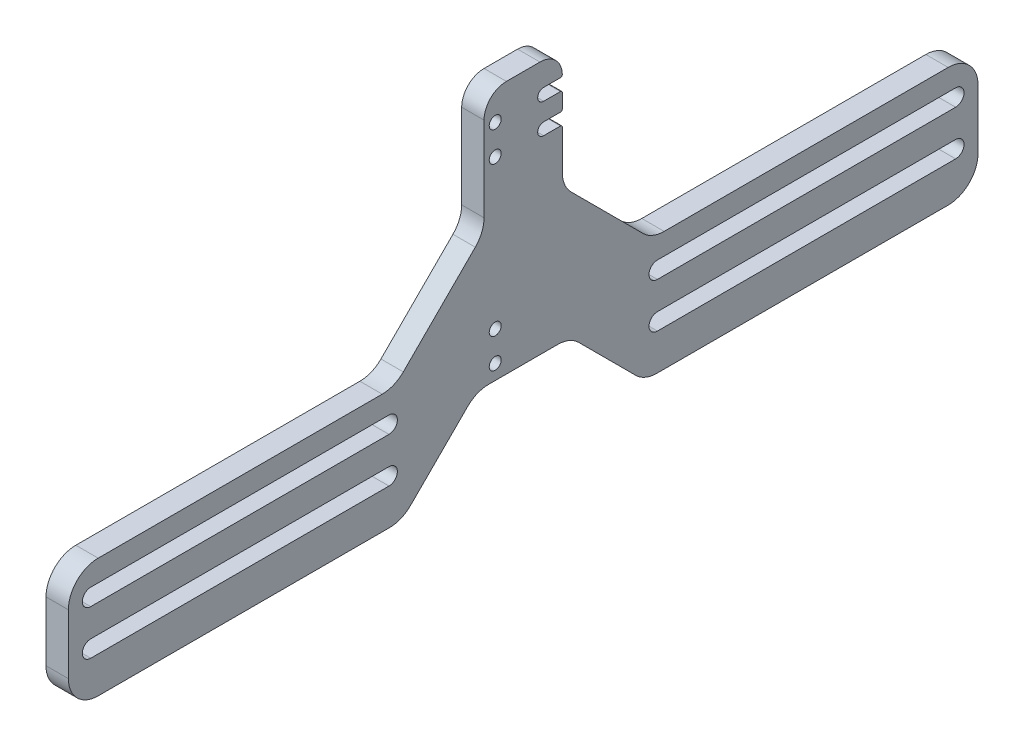
SolidWorks part; units mm, degrees
material "6061-T6 (SS)"
ref_plane "Front Plane" through (0, 0, 0) normal (0, 0, 1) x (1, 0, 0)
ref_plane "Top Plane" through (0, 0, 0) normal (0, 1, 0) x (1, 0, 0)
ref_plane "Right Plane" through (0, 0, 0) normal (1, 0, 0) x (0, 0, -1)
sketch "Sketch1" plane through (0, 0, 0) normal (1, 0, 0) x (0, 0, -1)
  line L0 (-193.675, 0) -> (193.675, 0)
  line L1 (193.675, 0) -> (193.675, 50.8)
  line L2 (193.675, 50.8) -> (54.7688, 50.8)
  line L5 (16.6687, 139.7) -> (-16.6687, 139.7)
  line L8 (-54.7688, 50.8) -> (-193.675, 50.8)
  line L9 (-193.675, 50.8) -> (-193.675, 0)
  line L10 (0, 139.7) -> (0, 0) construction
  line L13 (-16.6687, 139.7) -> (-16.6687, 88.9)
  line L14 (-16.6687, 88.9) -> (-54.7688, 50.8)
  line L15 (16.6687, 139.7) -> (16.6688, 88.9)
  line L16 (16.6688, 88.9) -> (54.7688, 50.8)
  dimension "D1" = 50.8
  dimension "D2" = 33.3375
  dimension "D3" = 193.675
  dimension "D4" = 45
  dimension "D5" = 50.8
  dimension "D6" = 139.7
extrude "Boss-Extrude1" add sketch "Sketch1" along normal blind 9.525
sketch "Sketch2" plane through (9.525, 0, 0) normal (1, 0, 0) x (0, 0, -1)
  line L0 (-184.15, 38.1) -> (-57.15, 38.1) construction
  line L1 (-184.15, 19.05) -> (-57.15, 19.05) construction
  line L4 (-193.675, 0) -> (193.675, 0) construction
  line L5 (-184.15, 34.5281) -> (-57.15, 34.5281)
  line L6 (-184.15, 15.4781) -> (-57.15, 15.4781)
  line L7 (-184.15, 41.6719) -> (-57.15, 41.6719)
  line L8 (-184.15, 22.6219) -> (-57.15, 22.6219)
  arc A0 (-184.15, 34.5281) -> (-184.15, 41.6719) centre (-184.15, 38.1) cw
  arc A1 (-57.15, 34.5281) -> (-57.15, 41.6719) centre (-57.15, 38.1) ccw
  arc A2 (-184.15, 15.4781) -> (-184.15, 22.6219) centre (-184.15, 19.05) cw
  arc A3 (-57.15, 15.4781) -> (-57.15, 22.6219) centre (-57.15, 19.05) ccw
  dimension "D1" = 19.05
  dimension "D2" = 19.05
  dimension "D3" = 184.15
  dimension "D4" = 127
  dimension "D5" = 3.5719
  dimension "D6" = 3.5719
extrude "Cut-Extrude1" cut sketch "Sketch2" against normal through all
mirror "Mirror1" about plane through (0, 0, 0) normal (0, 0, 1) of "Cut-Extrude1"
sketch "Sketch4" plane through (9.525, 0, 0) normal (1, 0, 0) x (0, 0, -1)
  line L9 (-193.675, 0) -> (193.675, 0) construction
  line L10 (-51.6872, 0) -> (-19.9372, 31.75)
  line L11 (-19.9372, 31.75) -> (19.9372, 31.75)
  line L12 (19.9372, 31.75) -> (51.6872, 0)
  line L14 (51.6872, 0) -> (-51.6872, 0)
  line L16 (0, 31.75) -> (0, 0) construction
  line L18 (-16.6687, 88.9) -> (-54.7688, 50.8) construction
  dimension "D1" = 38.1
  dimension "D2" = 31.75
extrude "Cut-Extrude3" cut sketch "Sketch4" against normal through all
hole_wizard "#10 Clearance Hole1" positions "Sketch5" profile "Sketch6" hole size "#10" standard "ANSI Inch" end condition through all
sketch "Sketch5" plane through (9.525, 0, 0) normal (1, 0, 0) x (0, 0, -1)
  line L0 (0, 139.7) -> (0, 190.4752) construction
  line L1 (16.6687, 139.7) -> (-16.6687, 139.7) construction
  line L4 (16.6687, 139.7) -> (-16.6687, 139.7) construction
  line L5 (-11.9062, 38.1) -> (-11.9062, 114.3) construction
  line L6 (-16.6687, 139.7) -> (-16.6687, 88.9) construction
  point P0 (-11.9062, 127)
  point P4 (11.9062, 127)
  point P6 (-11.9062, 114.3)
  point P8 (-11.9062, 38.1)
  point P42 (11.9062, 114.3)
  point P49 (-11.9063, 50.8)
  dimension "D1" = 4.7625
  dimension "D2" = 12.7
  dimension "D3" = 12.7
  dimension "D4" = 101.6
  dimension "D5" = 12.7
sketch "Sketch6" plane through (9.525, 127, 11.9062) normal (0, 1, 0) x (0, 0, -1)
  line L0 (0, 0) -> (0, 9.525)
  line L1 (0, 9.525) -> (2.5527, 9.525)
  line L2 (2.5527, 9.525) -> (2.5527, 0)
  line L5 (2.5527, 0) -> (0, 0)
  line L11 (0, -6.35) -> (0, 107.95) construction
  dimension "Thru Hole Dia." = 5.1054
  dimension "Thru Hole Depth" = 9.525
fillet "Fillet1" radius 9.525 2 edges at (4.7625, 139.7, -16.6687) (4.7625, 139.7, 16.6687)
fillet "Fillet2" radius 12.7 12 edges at (4.7625, 50.8, 193.675) (4.7625, 0, 193.675) (4.7625, 0, -193.675) (4.7625, 50.8, -193.675) (4.7625, 0, -51.6872) (4.7625, 31.75, -19.9372) (4.7625, 31.75, 19.9372) (4.7625, 0, 51.6872) (4.7625, 50.8, -54.7688) (4.7625, 88.9, -16.6688) (4.7625, 50.8, 54.7688) (4.7625, 88.9, 16.6687)
sketch "Sketch7" plane through (9.525, 0, 0) normal (1, 0, 0) x (0, 0, -1)
  line L1 (11.9062, 127) -> (8.7312, 127) construction
  line L2 (11.9062, 127) -> (16.6688, 127) construction
  line L5 (16.6688, 94.1605) -> (16.6687, 130.175) construction
  line L8 (16.6688, 114.3) -> (11.9062, 114.3) construction
  line L9 (11.9062, 114.3) -> (8.7312, 114.3) construction
  line L16 (11.9062, 129.5527) -> (16.6688, 129.5527)
  line L17 (11.9062, 129.5527) -> (8.7312, 129.5527)
  line L20 (16.6688, 116.8527) -> (11.9062, 116.8527)
  line L21 (11.9062, 116.8527) -> (8.7312, 116.8527)
  line L28 (11.9062, 124.4473) -> (16.6688, 124.4473)
  line L29 (11.9062, 124.4473) -> (8.7312, 124.4473)
  line L32 (16.6688, 111.7473) -> (11.9062, 111.7473)
  line L33 (11.9062, 111.7473) -> (8.7312, 111.7473)
  arc A2 (16.6688, 129.5527) -> (16.6688, 124.4473) centre (16.6688, 127) cw
  arc A3 (8.7312, 129.5527) -> (8.7312, 124.4473) centre (8.7312, 127) ccw
  arc A6 (16.6688, 116.8527) -> (16.6688, 111.7473) centre (16.6688, 114.3) cw
  arc A7 (8.7312, 116.8527) -> (8.7312, 111.7473) centre (8.7312, 114.3) ccw
  dimension "D1" = 3.175
extrude "Cut-Extrude4" cut sketch "Sketch7" against normal through all
fillet "Fillet3" radius 0.7937 4 edges at (4.7625, 111.7473, -16.6688) (4.7625, 116.8527, -16.6688) (4.7625, 124.4473, -16.6688) (4.7625, 129.5527, -16.6688)
